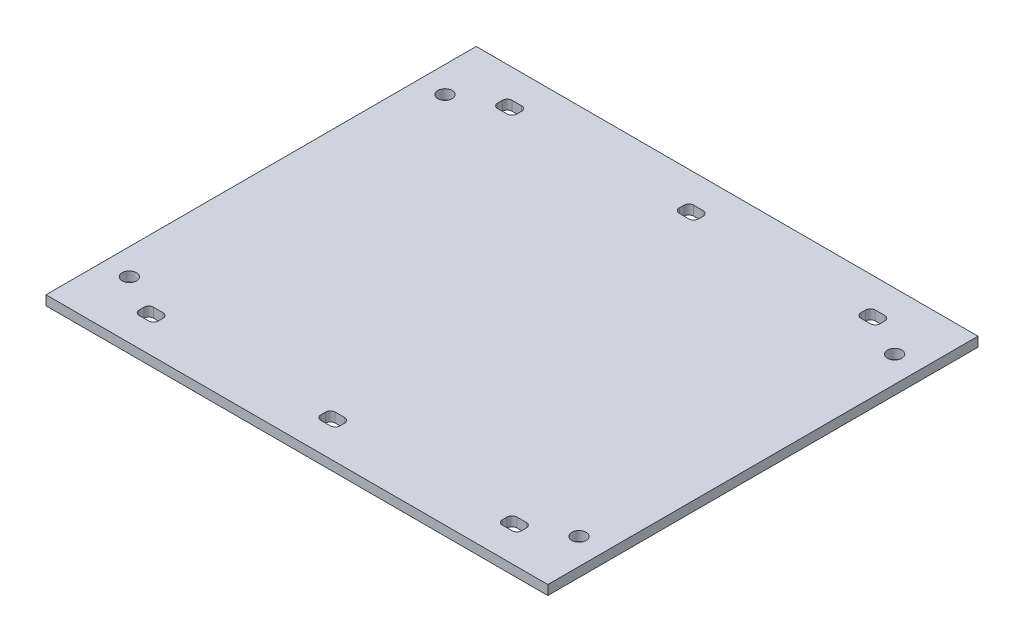
SolidWorks part; units mm, degrees
ref_plane "Front Plane" through (0, 0, 0) normal (0, 0, 1) x (1, 0, 0)
ref_plane "Top Plane" through (0, 0, 0) normal (0, 1, 0) x (1, 0, 0)
ref_plane "Right Plane" through (0, 0, 0) normal (1, 0, 0) x (0, 0, -1)
sketch "Sketch1" plane through (0, 0, 0) normal (0, 1, 0) x (1, 0, 0)
  line L1 (0, 0) -> (105, 0)
  line L2 (0, 0) -> (0, 90)
  line L3 (0, 90) -> (105, 90)
  line L4 (105, 0) -> (105, 90)
  dimension "D1" = 105
  dimension "D2" = 90
extrude "Boss-Extrude1" add sketch "Sketch1" along normal blind 2
hole_wizard "M3 Clearance Hole1" positions "Sketch3" profile "Sketch2" hole size "M3" standard "ANSI Metric"
sketch "Sketch3" plane through (0, 2, 0) normal (0, 1, 0) x (1, 0, 0)
  line L0 (0, 90) -> (0, 0) construction
  line L1 (105, 0) -> (105, 90) construction
  line L2 (0, 0) -> (105, 0) construction
  line L3 (105, 90) -> (0, 90) construction
  point P0 (5.46, 11.98)
  point P2 (5.46, 78.02)
  point P4 (99.54, 78.02)
  point P6 (99.54, 11.98)
  dimension "D1" = 66.04
  dimension "D2" = 66.04
  dimension "D3" = 94.08
  dimension "D4" = 94.08
  dimension "D5" = 5.46
  dimension "D6" = 5.46
  dimension "D7" = 11.98
  dimension "D8" = 11.98
  dimension "D9" = 11.98
  dimension "D10" = 11.98
  dimension "D11" = 5.46
sketch "Sketch2" plane through (5.46, 2, -11.98) normal (1, 0, 0) x (0, 0, 1)
  line L0 (0, 0) -> (0, 2.9013)
  line L1 (0, 2.9013) -> (1.5, 2)
  line L2 (1.5, 2) -> (1.5, 0)
  line L5 (1.5, 0) -> (0, 0)
  line L10 (0, 2.9013) -> (-1.5, 2) construction
  line L11 (0, -6.35) -> (0, 107.95) construction
  dimension "Hole Dia." = 3
  dimension "Hole Depth" = 2
  dimension "Drill Angle" = 118
sketch "Sketch4" plane through (0, 2, 0) normal (0, 1, 0) x (1, 0, 0)
  line L0 (0, 90) -> (0, 0) construction
  line L1 (12.5, 81) -> (16.5, 81)
  line L2 (12.5, 81) -> (12.5, 84)
  line L3 (12.5, 84) -> (16.5, 84)
  line L4 (16.5, 81) -> (16.5, 84)
  line L5 (105, 90) -> (0, 90) construction
  dimension "D1" = 3
  dimension "D2" = 4
  dimension "D3" = 12.5
  dimension "D4" = 6
extrude "Cut-Extrude1" cut sketch "Sketch4" against normal through all
fillet "Fillet1" radius 1 1 edges at (12.5, 1, -84)
fillet "Fillet2" radius 1 1 edges at (12.5, 1, -81)
fillet "Fillet3" radius 1 1 edges at (16.5, 1, -84)
fillet "Fillet4" radius 1 1 edges at (16.5, 1, -81)
pattern_linear "LPattern1" count 2 spacing 75 along (0, 0, 1) count 3 spacing 38 along (1, 0, 0) of "Cut-Extrude1", "Fillet1", "Fillet2", "Fillet3", "Fillet4"
